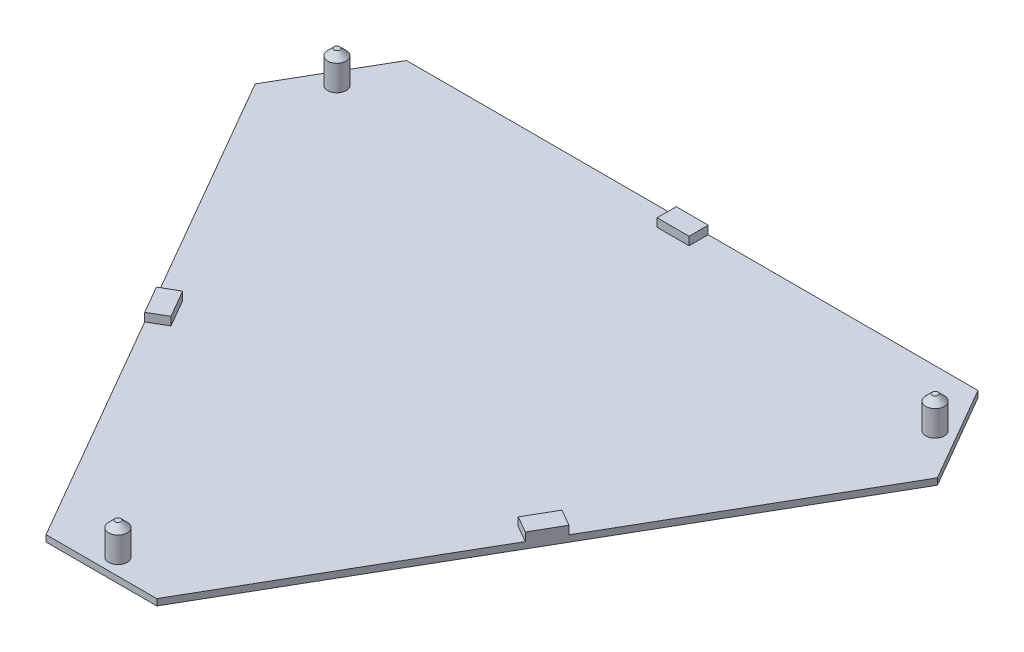
SolidWorks part; units mm, degrees
ref_plane "Plan de face" through (0, 0, 0) normal (0, 0, 1) x (1, 0, 0)
ref_plane "Plan de dessus" through (0, 0, 0) normal (0, 1, 0) x (1, 0, 0)
ref_plane "Plan de droite" through (0, 0, 0) normal (1, 0, 0) x (0, 0, -1)
sketch "Esquisse2" plane through (0, 0, 0) normal (0, 1, 0) x (1, 0, 0)
  line L3 (-44.6795, 35.7957) -> (-53.3397, 20.7957) construction
  line L4 (53.3397, 20.7957) -> (44.6795, 35.7957) construction
  line L6 (-53.3397, 20.7957) -> (-44.6795, 35.7957)
  line L7 (44.6795, 35.7957) -> (53.3397, 20.7957)
  line L8 (8.6603, -56.5914) -> (-8.6603, -56.5914)
  line L9 (-53.3397, 20.7957) -> (-8.6603, -56.5914)
  line L10 (8.6603, -56.5914) -> (53.3397, 20.7957)
  line L11 (44.6795, 35.7957) -> (-44.6795, 35.7957)
  line L12 (53.3397, 20.7957) -> (8.6603, -56.5914) construction
  line L14 (-8.6603, -56.5914) -> (-53.3397, 20.7957) construction
  line L15 (-44.6795, 35.7957) -> (44.6795, 35.7957) construction
  point P16 (0, 0)
extrude "Boss.-Extru.2" add sketch "Esquisse2" along normal blind 1
sketch "Esquisse3" plane through (0, 1, 0) normal (0, 1, 0) x (1, 0, 0)
  circle A0 centre (0, -54) radius 1.45
  circle A1 centre (-46.7654, 27) radius 1.45
  circle A2 centre (46.7654, 27) radius 1.45
  circle A3 centre (0, -54) radius 1.6 construction
  point P4 (0, -60.6409)
  point P9 (0, 0)
  dimension "D1" = 2.9
  dimension "D2" = 0
  dimension "D3" = 3
extrude "Boss.-Extru.3" add sketch "Esquisse3" along normal blind 5
chamfer "Chanfrein1" distance 1 angle 45 3 edges at (-46.7654, 6, -25.55) (46.7654, 6, -25.55) (0, 6, 55.45)
sketch "Esquisse4" plane through (0, 1, 0) normal (0, 1, 0) x (1, 0, 0)
  line L0 (44.6795, 35.7957) -> (-44.6795, 35.7957) construction
  line L1 (-2.5, 35.7957) -> (2.5, 35.7957)
  line L2 (-2.5, 35.7957) -> (-2.5, 32.7957)
  line L3 (-2.5, 32.7957) -> (2.5, 32.7957)
  line L4 (2.5, 35.7957) -> (2.5, 32.7957)
  line L5 (32.25, -15.7328) -> (29.75, -20.0629)
  line L6 (32.25, -15.7328) -> (29.6519, -14.2328)
  line L7 (29.6519, -14.2328) -> (27.1519, -18.5629)
  line L8 (29.75, -20.0629) -> (27.1519, -18.5629)
  line L9 (-29.75, -20.0629) -> (-32.25, -15.7328)
  line L10 (-29.75, -20.0629) -> (-27.1519, -18.5629)
  line L11 (-27.1519, -18.5629) -> (-29.6519, -14.2328)
  line L12 (-32.25, -15.7328) -> (-29.6519, -14.2328)
  point P6 (0, 35.7957)
  point P18 (0, 0)
  dimension "D1" = 5
  dimension "D2" = 3
  dimension "D3" = 3
extrude "Boss.-Extru.4" add sketch "Esquisse4" against normal up to surface (1 mm away) and the other way blind 1.3 up to face at (0, 0, 0)
